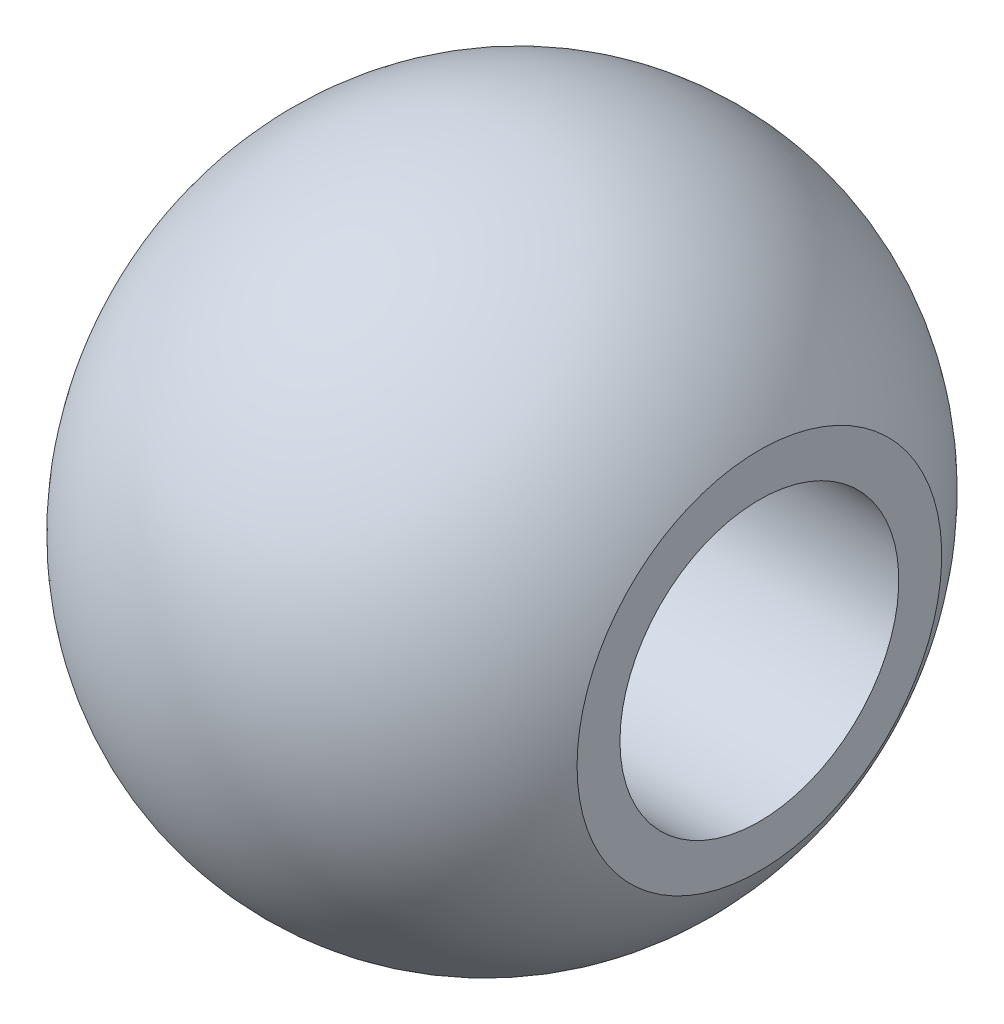
SolidWorks part; units mm, degrees
ref_plane "Front Plane" through (0, 0, 0) normal (0, 0, 1) x (1, 0, 0)
ref_plane "Top Plane" through (0, 0, 0) normal (0, 1, 0) x (1, 0, 0)
ref_plane "Right Plane" through (0, 0, 0) normal (1, 0, 0) x (0, 0, -1)
sketch "Sketch2" plane through (0, 0, 0) normal (0, 1, 0) x (1, 0, 0)
  line L0 (-9.0492, 0) -> (8.6422, 0) construction
  line L2 (-6, 4.25) -> (-6, 0)
  line L3 (-6, 0) -> (6, 0)
  line L4 (6, 0) -> (6, 4.25)
  arc A1 (-6, 4.25) -> (6, 4.25) centre (0, 0.8777) cw
  dimension "D1" = 12
revolve "Revolve1" add sketch "Sketch2" angle 360 about L0
sketch "Sketch3" plane through (-6, 0, 0) normal (-1, 0, 0) x (0, 0, 1)
  circle A0 centre (0, 0) radius 3.25
  dimension "D1" = 6.5
extrude "Cut-Extrude1" cut sketch "Sketch3" against normal up to surface (12 mm away) up to face at (6, 0, 4.25)
